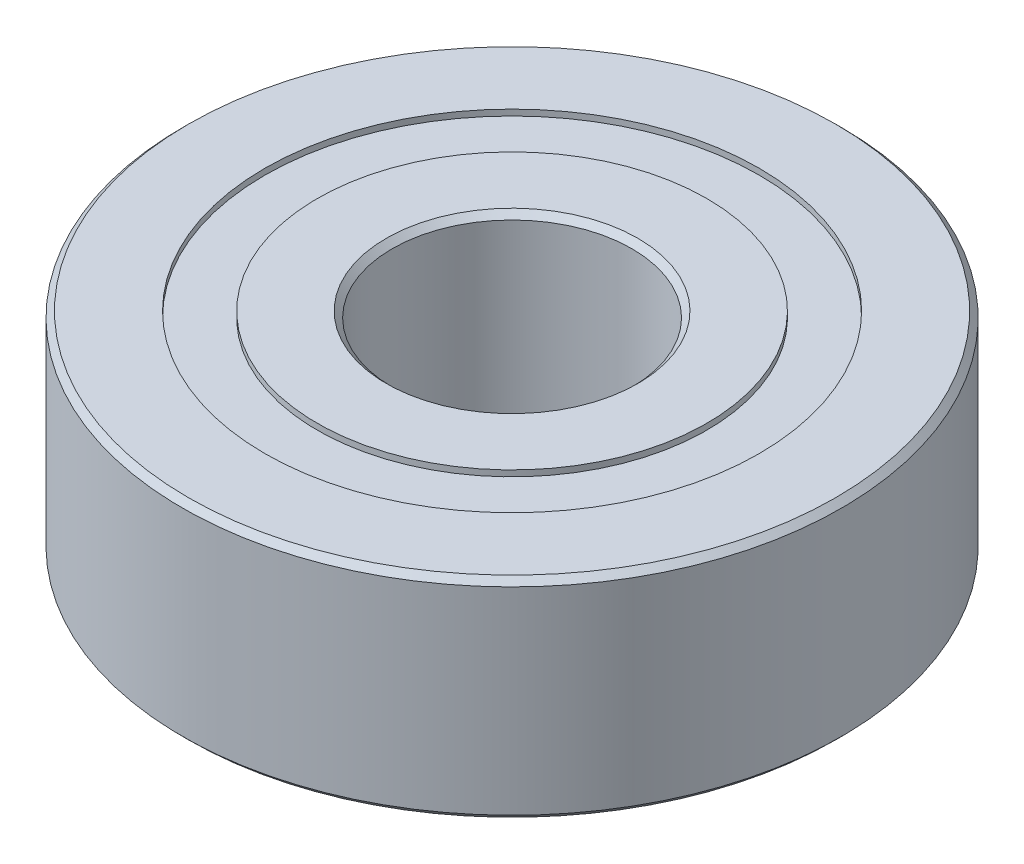
SolidWorks part; units mm, degrees
ref_plane "Front Plane" through (0, 0, 0) normal (0, 0, 1) x (1, 0, 0)
ref_plane "Top Plane" through (0, 0, 0) normal (0, 1, 0) x (1, 0, 0)
ref_plane "Right Plane" through (0, 0, 0) normal (1, 0, 0) x (0, 0, -1)
sketch "Sketch1" plane through (0, 0, 0) normal (0, 0, 1) x (1, 0, 0)
  line L0 (11, 6.8) -> (10.8, 7)
  line L1 (10.8, 7) -> (8.25, 7)
  line L2 (8.25, 7) -> (8.25, 6.8)
  line L3 (8.25, 6.8) -> (6.5, 6.8)
  line L4 (6.5, 6.8) -> (6.5, 7)
  line L5 (6.5, 7) -> (4.2, 7)
  line L6 (4.2, 7) -> (4, 6.8)
  line L7 (4, 6.8) -> (4, 0.2)
  line L8 (4, 0.2) -> (4.2, 0)
  line L9 (4.2, 0) -> (6.5, 0)
  line L10 (6.5, 0) -> (6.5, 0.2)
  line L11 (6.5, 0.2) -> (8.25, 0.2)
  line L12 (8.25, 0.2) -> (8.25, 0)
  line L13 (8.25, 0) -> (10.8, 0)
  line L14 (10.8, 0) -> (11, 0.2)
  line L15 (11, 0.2) -> (11, 6.8)
  line L16 (0, 7) -> (0, 0) construction
revolve "Revolve1" add sketch "Sketch1" angle 360 about L16
